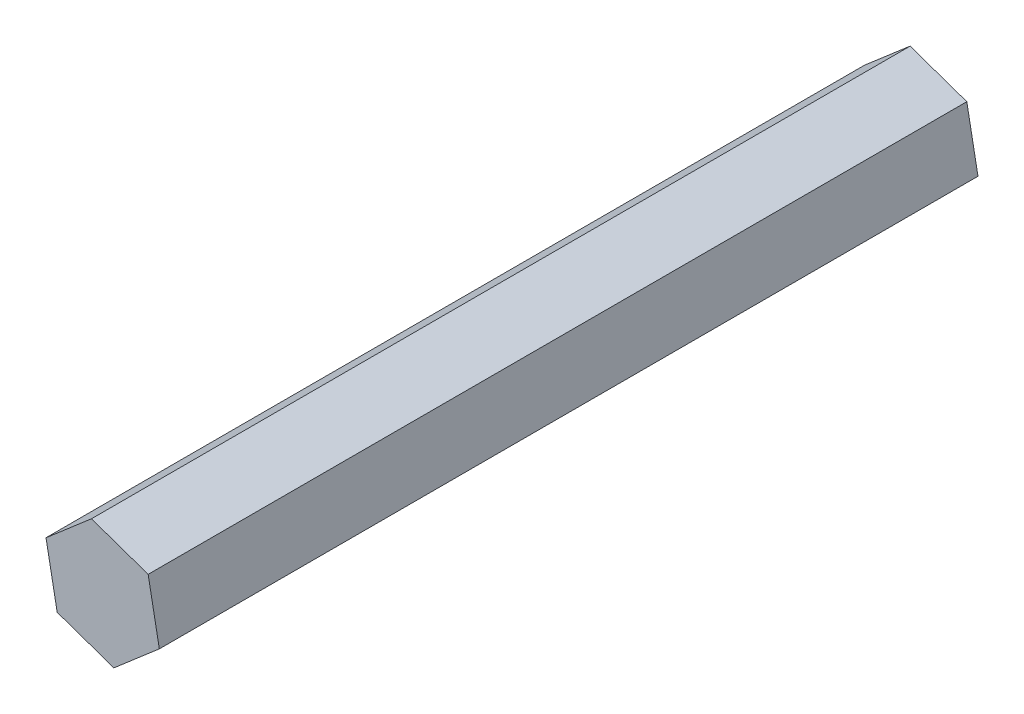
SolidWorks part; units mm, degrees
ref_plane "Front Plane" through (0, 0, 0) normal (0, 0, 1) x (1, 0, 0)
ref_plane "Top Plane" through (0, 0, 0) normal (0, 1, 0) x (1, 0, 0)
ref_plane "Right Plane" through (0, 0, 0) normal (1, 0, 0) x (0, 0, -1)
sketch "Sketch1" plane through (0, 0, 0) normal (0, 0, 1) x (1, 0, 0)
  line L1 (5.5548, 4.7862) -> (-1.3676, 7.2037)
  line L2 (-1.3676, 7.2037) -> (-6.9224, 2.4175)
  line L3 (-6.9224, 2.4175) -> (-5.5548, -4.7862)
  line L4 (-5.5548, -4.7862) -> (1.3676, -7.2037)
  line L5 (1.3676, -7.2037) -> (6.9224, -2.4175)
  line L6 (6.9224, -2.4175) -> (5.5548, 4.7862)
  circle A0 centre (0, 0) radius 6.35 construction
  dimension "D1" = 12.7
extrude "Boss-Extrude1" add sketch "Sketch1" along normal blind 100
